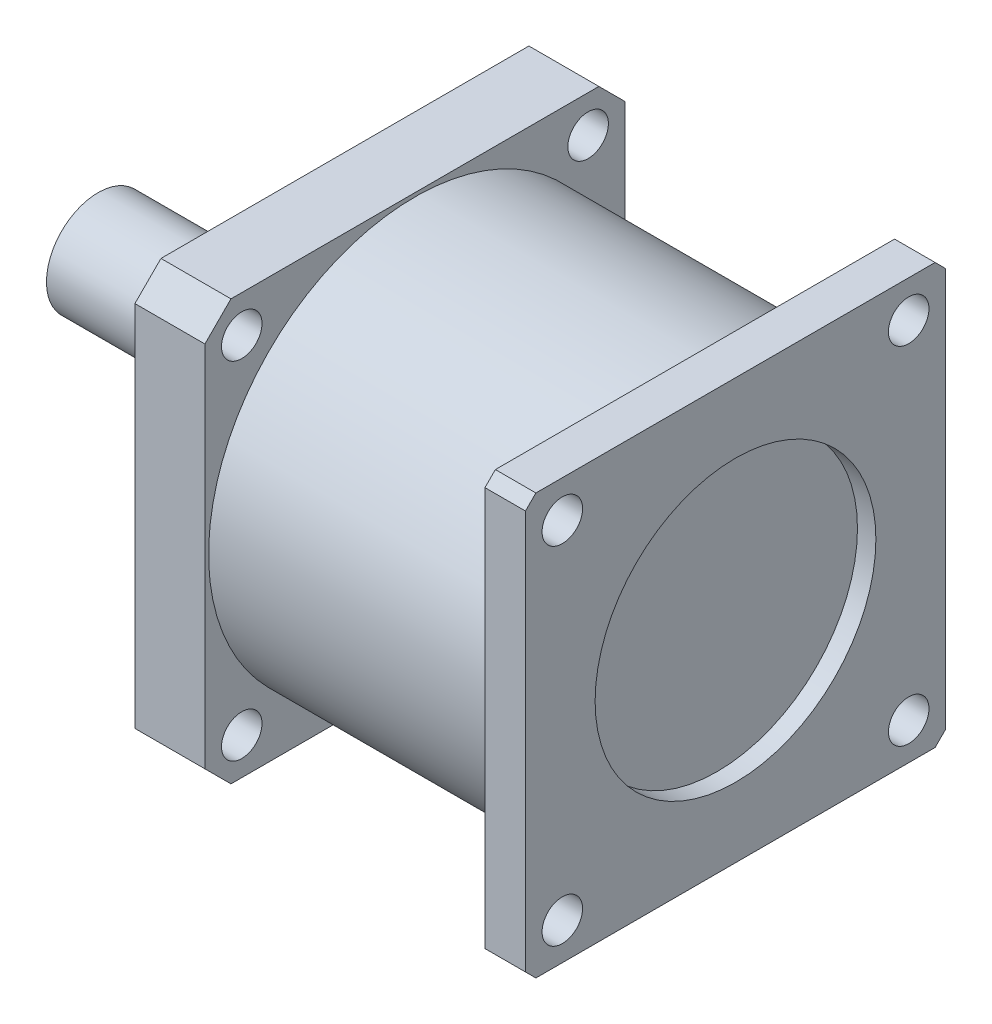
SolidWorks part; units mm, degrees
ref_plane "Front Plane" through (0, 0, 0) normal (0, 0, 1) x (1, 0, 0)
ref_plane "Top Plane" through (0, 0, 0) normal (0, 1, 0) x (1, 0, 0)
ref_plane "Right Plane" through (0, 0, 0) normal (1, 0, 0) x (0, 0, -1)
sketch "Sketch1" plane through (0, 0, 0) normal (1, 0, 0) x (0, 0, -1)
  circle A0 centre (0, 0) radius 28
extrude "Boss-Extrude1" add sketch "Sketch1" along normal blind 38
sketch "Sketch2" plane through (38, 0, 0) normal (1, 0, 0) x (0, 0, -1)
  line L1 (28.5, 0) -> (28.5, 28.5)
  line L2 (28.5, 28.5) -> (-28.5, 28.5)
  line L3 (-28.5, 28.5) -> (-28.5, -28.5)
  line L4 (-28.5, -28.5) -> (28.5, -28.5)
  line L5 (28.5, -28.5) -> (28.5, 0)
extrude "Boss-Extrude2" add sketch "Sketch2" along normal blind 5.5
sketch "Sketch4" plane through (43.5, 0, 0) normal (1, 0, 0) x (0, 0, -1)
  circle A0 centre (0, 0) radius 19.05
extrude "Cut-Extrude1" cut sketch "Sketch4" against normal blind 2.5
sketch "Sketch5" plane through (43.5, 0, 0) normal (1, 0, 0) x (0, 0, -1)
  line L1 (-27.7929, 27.7929) -> (-27.0858, 28.5)
  line L2 (28.5, 28.5) -> (-28.5, 28.5) construction
  line L3 (-27.0858, 28.5) -> (-28.5, 27.0858)
  line L4 (-28.5, 28.5) -> (-28.5, -28.5) construction
  line L5 (-28.5, 27.0858) -> (-28.5, 28.5)
  line L6 (-27.0858, 28.5) -> (-28.5, 28.5)
extrude "Cut-Extrude2" cut sketch "Sketch5" against normal blind 5.5 contours L3 L5 L6
pattern_circular "CirPattern1" count 4 over 360 about axis through (0, 0, 0) along (1, 0, 0) of "Cut-Extrude2"
sketch "Sketch6" plane through (0, 0, 0) normal (-1, 0, 0) x (0, 0, 1)
  line L1 (28.5, 27.0858) -> (28.5, -27.0858) construction
  line L2 (28.5, 0) -> (28.5, -28.5)
  line L3 (28.5, -28.5) -> (-28.5, -28.5)
  line L4 (-28.5, -28.5) -> (-28.5, 28.5)
  line L5 (-28.5, 28.5) -> (28.5, 28.5)
  line L6 (28.5, 28.5) -> (28.5, 0)
extrude "Boss-Extrude3" add sketch "Sketch6" along normal blind 9.5
sketch "Sketch7" plane through (-9.5, 0, 0) normal (-1, 0, 0) x (0, 0, 1)
  line L2 (28.5, 28.5) -> (-28.5, 28.5) construction
  line L3 (-24.9645, 28.5) -> (-28.5, 24.9645)
  line L4 (-28.5, 28.5) -> (-28.5, -28.5) construction
  line L5 (-28.5, 24.9645) -> (-28.5, 28.5)
  line L6 (-24.9645, 28.5) -> (-28.5, 28.5)
extrude "Cut-Extrude3" cut sketch "Sketch7" against normal blind 9.5
pattern_circular "CirPattern2" count 4 over 360 about axis through (0, 0, 0) along (1, 0, 0) of "Cut-Extrude3"
sketch "Sketch8" plane through (-9.5, 0, 0) normal (-1, 0, 0) x (0, 0, 1)
  circle A0 centre (0, 0) radius 20
extrude "Boss-Extrude4" add sketch "Sketch8" along normal blind 2.5
sketch "Sketch9" plane through (-12, 0, 0) normal (-1, 0, 0) x (0, 0, 1)
  circle A0 centre (0, 0) radius 7.5
extrude "Boss-Extrude5" add sketch "Sketch9" along normal blind 1
sketch "Sketch10" plane through (-13, 0, 0) normal (-1, 0, 0) x (0, 0, 1)
  circle A0 centre (0, 0) radius 7
extrude "Boss-Extrude6" add sketch "Sketch10" along normal blind 30
sketch "Sketch11" plane through (-43, 0, 0) normal (-1, 0, 0) x (0, 0, 1)
  circle A0 centre (0, 0) radius 2
extrude "Cut-Extrude4" cut sketch "Sketch11" against normal blind 10
sketch "Sketch12" plane through (43.5, 0, 0) normal (1, 0, 0) x (0, 0, -1)
  line L0 (0, 0) -> (23.5, 0)
  line L1 (23.5, 0) -> (23.5, 23.5)
  line L2 (23.5, 23.5) -> (-23.5, 23.5)
  line L3 (-23.5, 23.5) -> (-23.5, -23.5)
  line L4 (-23.5, -23.5) -> (23.5, -23.5)
  line L5 (23.5, -23.5) -> (23.5, 0)
  circle A0 centre (-23.5, 23.5) radius 2.75
extrude "Cut-Extrude5" cut sketch "Sketch12" along a picked direction on the side against the normal blind 60 contours L2 A0 L3 | L3 A0 L2
pattern_circular "CirPattern3" count 4 over 360 about axis through (0, 0, 0) along (1, 0, 0) of "Cut-Extrude5"
